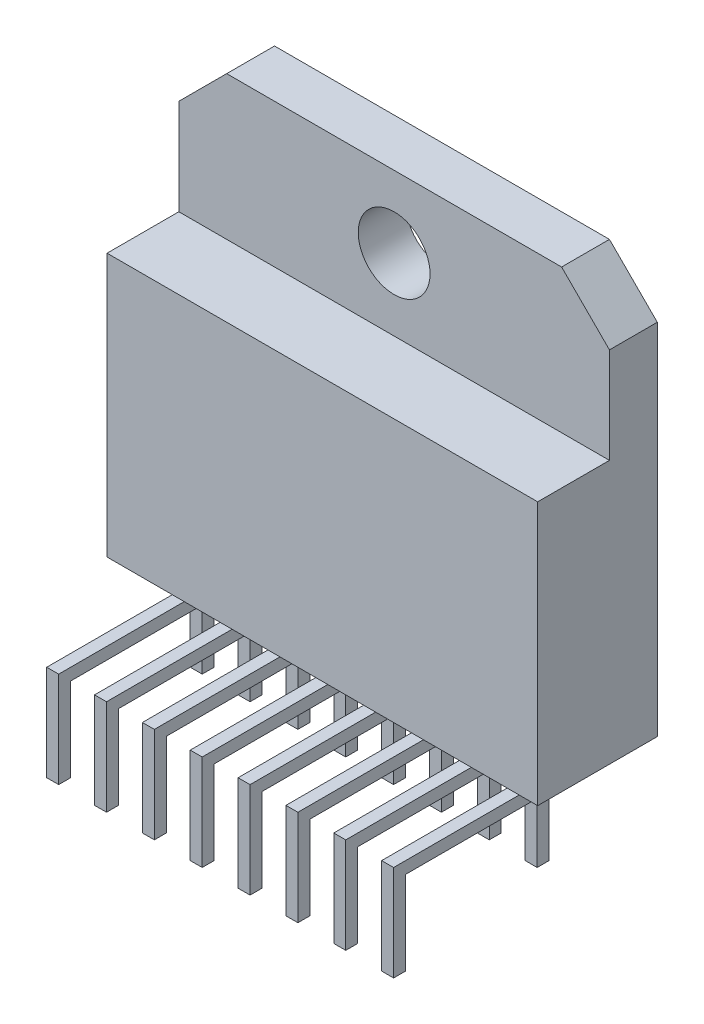
SolidWorks part; units mm, degrees
ref_plane "Front Plane" through (0, 0, 0) normal (0, 0, 1) x (1, 0, 0)
ref_plane "Top Plane" through (0, 0, 0) normal (0, 1, 0) x (1, 0, 0)
ref_plane "Right Plane" through (0, 0, 0) normal (1, 0, 0) x (0, 0, -1)
sketch "Sketch2" plane through (0, 0, 0) normal (1, 0, 0) x (0, 0, -1)
  line L0 (0, 0) -> (0, 17)
  line L1 (0, 17) -> (-2, 17)
  line L2 (-2, 17) -> (-2, 11)
  line L3 (-2, 11) -> (-5, 11)
  line L4 (-5, 11) -> (-5, 0)
  line L5 (-5, 0) -> (0, 0)
  dimension "D1" = 17
  dimension "D2" = 11
  dimension "D3" = 5
  dimension "D4" = 3
extrude "Boss-Extrude1" add sketch "Sketch2" along normal blind 18
sketch "Sketch3" plane through (0, 0, 2) normal (0, 0, 1) x (1, 0, 0)
  line L0 (18, 17) -> (0, 17) construction
  circle A0 centre (9, 14) radius 1.5
  dimension "D1" = 3
  dimension "D2" = 3
extrude "Cut-Extrude1" cut sketch "Sketch3" against normal through all
chamfer "Chamfer1" distance 2 angle 45 2 edges at (18, 17, 1) (0, 17, 1)
ref_plane "Plane1" through (2.227, 0, 0) normal (1, 0, 0) x (0, 0, -1)
sketch "Sketch4" plane through (2.227, 0, 0) normal (1, 0, 0) x (0, 0, -1)
  line L0 (-2.25, 0) -> (-2.25, -1)
  line L1 (-5, 0) -> (0, 0) construction
  line L2 (-2.25, -1) -> (-9.25, -1)
  line L3 (-9.25, -1) -> (-9.25, -4.5)
  line L4 (-9.25, -4.5) -> (-9.75, -4.5)
  line L5 (-9.75, -4.5) -> (-9.75, -0.5)
  line L6 (-9.75, -0.5) -> (-2.75, -0.5)
  line L7 (-2.75, -0.5) -> (-2.75, 0)
  line L8 (-2.75, 0) -> (-2.25, 0)
  dimension "D1" = 0.5
  dimension "D2" = 7
  dimension "D3" = 0.5
  dimension "D4" = 4
  dimension "D5" = 0.5
  dimension "D6" = 0.5
  dimension "D7" = 2.25
extrude "Boss-Extrude2" add sketch "Sketch4" along normal blind 0.5
pattern_linear "LPattern1" count 8 spacing 2 along (1, 0, 0) of "Boss-Extrude2"
ref_plane "Plane2" through (1.227, 0, 0) normal (1, 0, 0) x (0, 0, -1)
sketch "Sketch5" plane through (1.227, 0, 0) normal (1, 0, 0) x (0, 0, -1)
  line L1 (-2.25, 0) -> (-2.75, 0)
  line L2 (-2.75, 0) -> (-2.75, -4.5)
  line L3 (-2.75, -4.5) -> (-2.25, -4.5)
  line L4 (-2.25, -4.5) -> (-2.25, 0)
extrude "Boss-Extrude3" add sketch "Sketch5" along normal blind 0.5
pattern_linear "LPattern2" count 8 spacing 2 along (1, 0, 0) of "Boss-Extrude3"
